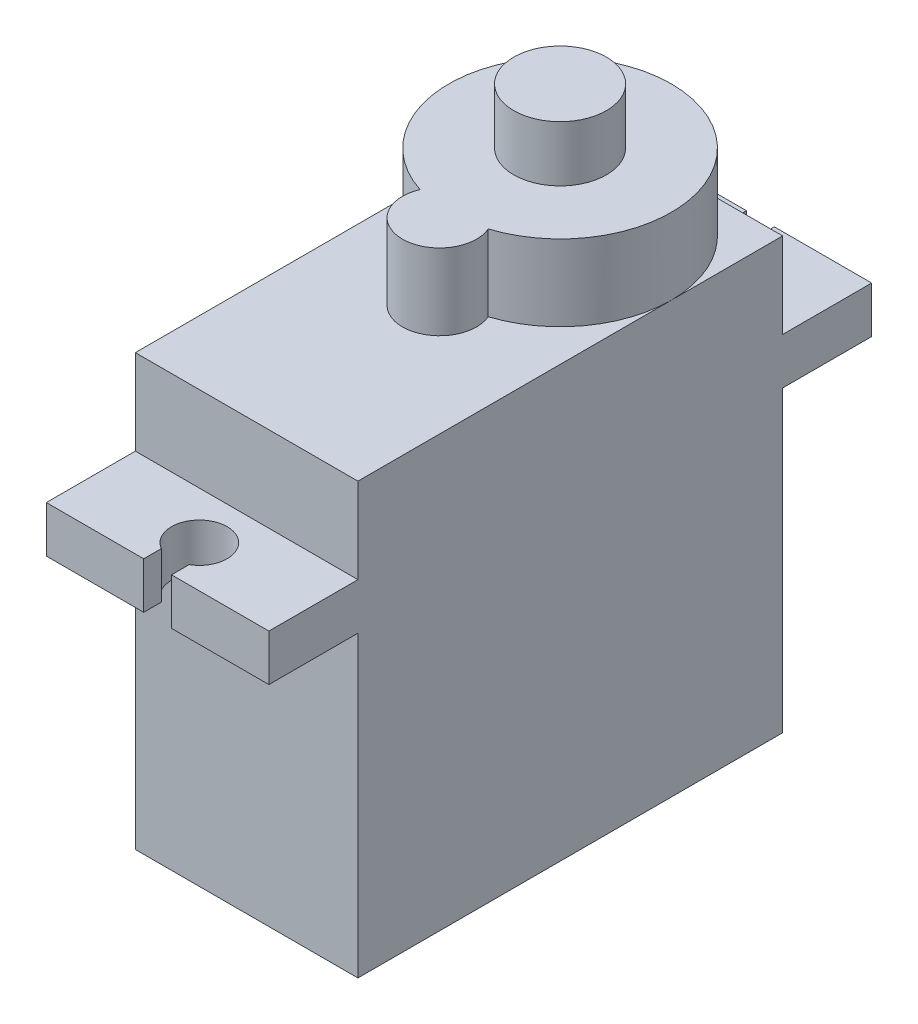
SolidWorks part; units mm, degrees
ref_plane "前视基准面" through (0, 0, 0) normal (0, 0, 1) x (1, 0, 0)
ref_plane "上视基准面" through (0, 0, 0) normal (0, 1, 0) x (1, 0, 0)
ref_plane "右视基准面" through (0, 0, 0) normal (1, 0, 0) x (0, 0, -1)
other "Configuration Table"
sketch "草图1" plane through (0, 0, 0) normal (0, 1, 0) x (1, 0, 0)
  line L1 (0, 0) -> (12, 0)
  line L2 (0, 0) -> (0, 22.9)
  line L3 (0, 22.9) -> (12, 22.9)
  line L4 (12, 0) -> (12, 22.9)
  dimension "D1" = 22.9
extrude "凸台-拉伸1" add sketch "草图1" along normal blind 23.2
sketch "草图2" plane through (0, 23.2, 0) normal (0, 1, 0) x (1, 0, 0)
  line L0 (6, 22.9) -> (6, 16.9)
  line L1 (6, 16.9) -> (6, 10.4)
  line L4 (0, 22.9) -> (0, 0)
  line L5 (0, 0) -> (12, 0)
  line L6 (12, 0) -> (12, 22.9)
  line L7 (12, 22.9) -> (0, 22.9)
  line L8 (0, 22.9) -> (0, 0)
  line L9 (0, 0) -> (12, 0)
  line L10 (12, 0) -> (12, 22.9)
  line L11 (12, 22.9) -> (0, 22.9)
  circle A0 centre (6, 16.9) radius 6
  circle A1 centre (6, 10.4) radius 2
  dimension "D3" = 12
  dimension "D2" = 12
  dimension "D1" = 0
extrude "凸台-拉伸2" add sketch "草图2" along normal blind 4.1
sketch "草图3" plane through (0, 27.3, 0) normal (0, 1, 0) x (1, 0, 0)
  circle A0 centre (6, 16.9) radius 2.5
  arc A2 (4.162, 11.1885) -> (7.838, 11.1885) centre (6, 10.4) ccw
  arc A3 (7.838, 11.1885) -> (4.162, 11.1885) centre (6, 16.9) ccw
  arc A4 (4.162, 11.1885) -> (7.838, 11.1885) centre (6, 10.4) ccw
  arc A5 (7.838, 11.1885) -> (4.162, 11.1885) centre (6, 16.9) ccw
  dimension "D2" = 5
  dimension "D3" = 6
  dimension "D1" = 0
extrude "凸台-拉伸3" add sketch "草图3" along normal blind 3 contours A0
sketch "草图4" plane through (0, 0, 0) normal (0, 0, 1) x (1, 0, 0)
  line L0 (6, 0) -> (6, 16.1)
  line L1 (0, 0) -> (12, 0) construction
  line L2 (0, 16.1) -> (12, 16.1)
  line L3 (0, 23.2) -> (0, 0) construction
  line L4 (12, 23.2) -> (12, 0) construction
  line L5 (12, 16.1) -> (12, 18.6)
  line L6 (12, 18.6) -> (0, 18.6)
  line L7 (0, 18.6) -> (0, 16.1)
extrude "凸台-拉伸4" add sketch "草图4" along normal blind 4.8 contours L7 L2 L5 L6
sketch "草图5" plane through (0, 18.6, 0) normal (0, 1, 0) x (1, 0, 0)
  line L0 (6, -4.8) -> (6, -2.55)
  line L3 (5.25, -3.849) -> (5.25, -4.8)
  line L4 (12, 0) -> (0, 0)
  line L5 (0, 0) -> (0, -4.8)
  line L6 (0, -4.8) -> (12, -4.8)
  line L7 (12, -4.8) -> (12, 0)
  line L8 (12, 0) -> (0, 0)
  line L9 (0, 0) -> (0, -4.8)
  line L10 (0, -4.8) -> (12, -4.8)
  line L11 (12, -4.8) -> (12, 0)
  line L12 (6.75, -3.849) -> (6.75, -4.8)
  circle A0 centre (6, -2.55) radius 1.5
  dimension "D2" = 3
  dimension "D3" = 2.25
  dimension "D1" = 0
extrude "切除-拉伸1" cut sketch "草图5" against normal up to next
ref_plane "基准面1" through (0, 0, -11.45) normal (0, 0, 1) x (1, 0, 0)
mirror "镜向1" about plane through (0, 0, -11.45) normal (0, 0, 1) of "切除-拉伸1", "凸台-拉伸4"
sketch "草图6" plane through (0, 0, -22.9) normal (0, 0, -1) x (-1, 0, 0)
  line L0 (-6, 0) -> (-6, 3)
  line L1 (-6, 3) -> (-4, 3)
  line L2 (-6, 3) -> (-8, 3)
  line L3 (-8, 3) -> (-8, 0)
  line L4 (0, 0) -> (0, 16.1)
  line L5 (0, 16.1) -> (-12, 16.1)
  line L6 (-12, 16.1) -> (-12, 0)
  line L7 (-12, 0) -> (0, 0)
  line L8 (0, 0) -> (0, 16.1)
  line L9 (0, 16.1) -> (-12, 16.1)
  line L10 (-12, 16.1) -> (-12, 0)
  line L11 (-12, 0) -> (0, 0)
  line L12 (-4, 3) -> (-4, 0)
  line M11 (-12, 0) -> (0, 0)
  dimension "D2" = 3
  dimension "D3" = 2
  dimension "D1" = 0
extrude "凸台-拉伸5" add sketch "草图6" along normal blind 3 contours L2 L3 L0 M11 | L12 L1 L0 M11
